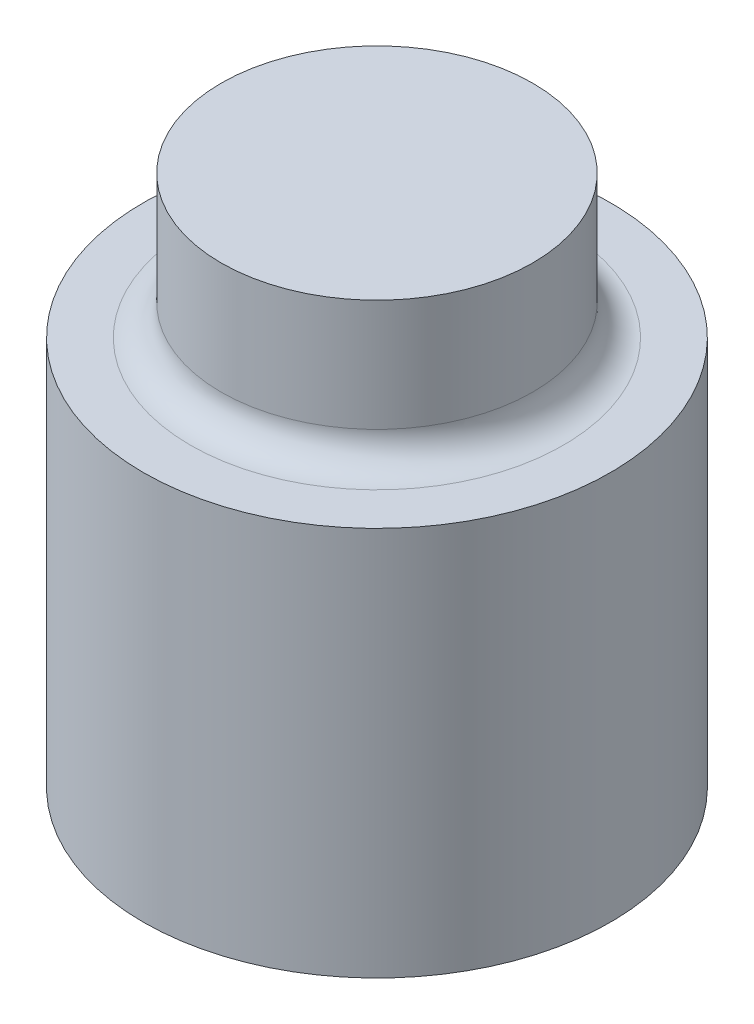
SolidWorks part; units mm, degrees
material "ABS"
ref_plane "Front Plane" through (0, 0, 0) normal (0, 0, 1) x (1, 0, 0)
ref_plane "Top Plane" through (0, 0, 0) normal (0, 1, 0) x (1, 0, 0)
ref_plane "Right Plane" through (0, 0, 0) normal (1, 0, 0) x (0, 0, -1)
sketch "Sketch1" plane through (0, 0, 0) normal (0, 1, 0) x (1, 0, 0)
  circle A0 centre (0, 0) radius 76.2
  dimension "D1" = 152.4
extrude "Boss-Extrude1" add sketch "Sketch1" along normal blind 127
sketch "Sketch2" plane through (0, 127, 0) normal (0, 1, 0) x (1, 0, 0)
  circle A0 centre (0, 0) radius 50.8
  dimension "D1" = 101.6
extrude "Boss-Extrude2" add sketch "Sketch2" along normal blind 46.482
fillet "Fillet1" radius 10 1 edges at (0, 127, 50.8)
